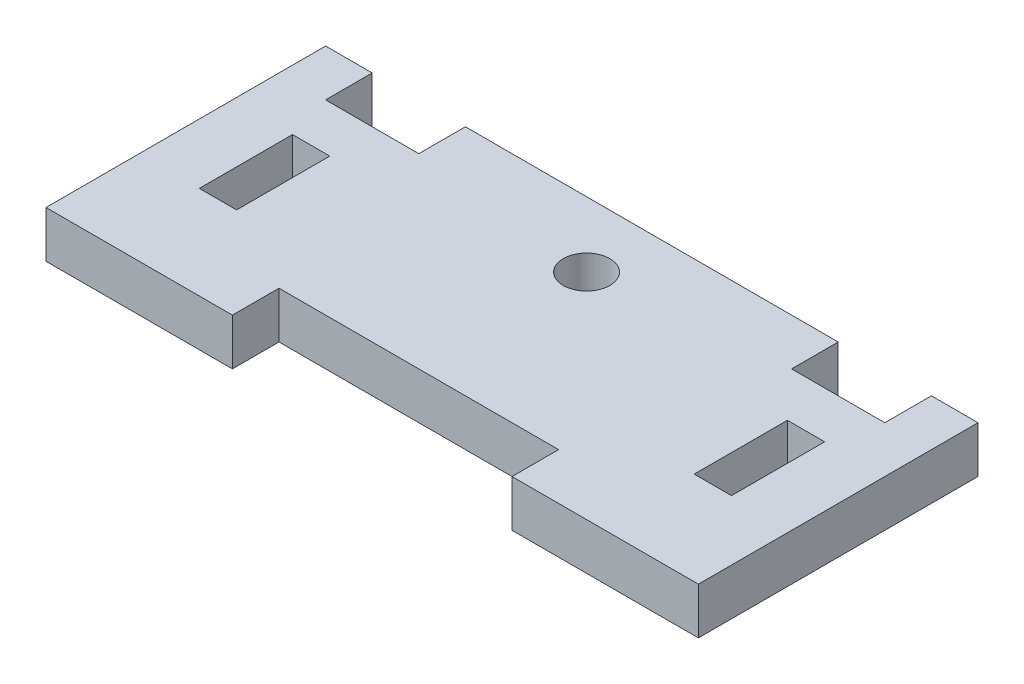
SolidWorks part; units mm, degrees
ref_plane "前视基准面" through (0, 0, 0) normal (0, 0, 1) x (1, 0, 0)
ref_plane "上视基准面" through (0, 0, 0) normal (0, 1, 0) x (1, 0, 0)
ref_plane "右视基准面" through (0, 0, 0) normal (1, 0, 0) x (0, 0, -1)
sketch "草图1" plane through (0, 0, 0) normal (0, 1, 0) x (1, 0, 0)
  line L0 (35, 46.2176) -> (35, -9.0474) construction
  line L1 (0, 0) -> (20, 0)
  line L2 (0, 0) -> (0, 30)
  line L3 (0, 30) -> (5, 30)
  line L4 (70, 0) -> (70, 30)
  line L5 (26, 47.137) -> (26, -6.8) construction
  line L6 (44, -7.9237) -> (44, 51.4275) construction
  line L7 (-10.323, 23) -> (85.3947, 23) construction
  line L8 (-11.5489, 14) -> (110.3712, 14) construction
  line L9 (6.45, 52.6533) -> (6.45, -5.472) construction
  line L10 (63.55, -5.472) -> (63.55, 52.6533) construction
  line L11 (15, 30) -> (55, 30)
  line L12 (50, 0) -> (70, 0)
  line L13 (55, 30) -> (55, 25)
  line L14 (55, 25) -> (65, 25)
  line L15 (65, 30) -> (65, 25)
  line L16 (59.55, 20) -> (63.55, 20)
  line L17 (5, 30) -> (5, 25)
  line L18 (5, 25) -> (15, 25)
  line L19 (15, 30) -> (15, 25)
  line L20 (6.45, 20) -> (10.45, 20)
  line L21 (20, 0) -> (20, 5)
  line L22 (20, 5) -> (50, 5)
  line L23 (50, 0) -> (50, 5)
  line L24 (65, 30) -> (70, 30)
  line L25 (6.45, 20) -> (6.45, 10)
  line L26 (6.45, 10) -> (10.45, 10)
  line L27 (10.45, 20) -> (10.45, 10)
  line L28 (59.55, 20) -> (59.55, 10)
  line L29 (59.55, 10) -> (63.55, 10)
  line L30 (63.55, 20) -> (63.55, 10)
  circle A0 centre (35, 23) radius 2.5
  point P33 (65, 27.5)
  point P42 (8.45, 10)
  point P43 (61.55, 10)
  dimension "D7" = 5
  dimension "D1" = 70
  dimension "D2" = 30
  dimension "D3" = 35
  dimension "D4" = 18
  dimension "D5" = 9
  dimension "D6" = 7
  dimension "D8" = 9
  dimension "D9" = 57.1
  dimension "D10" = 28.55
  dimension "D11" = 5
  dimension "D12" = 5
  dimension "D13" = 5
  dimension "D14" = 30
  dimension "D15" = 10
  dimension "D16" = 10
  dimension "D17" = 15
  dimension "D18" = 5
  dimension "D19" = 5
  dimension "D20" = 10
  dimension "D21" = 4
  dimension "D22" = 10
  dimension "D23" = 4
  dimension "D24" = 10
  dimension "D25" = 10
  dimension "D26" = 0
extrude "凸台-拉伸1" add sketch "草图1" along normal blind 5
